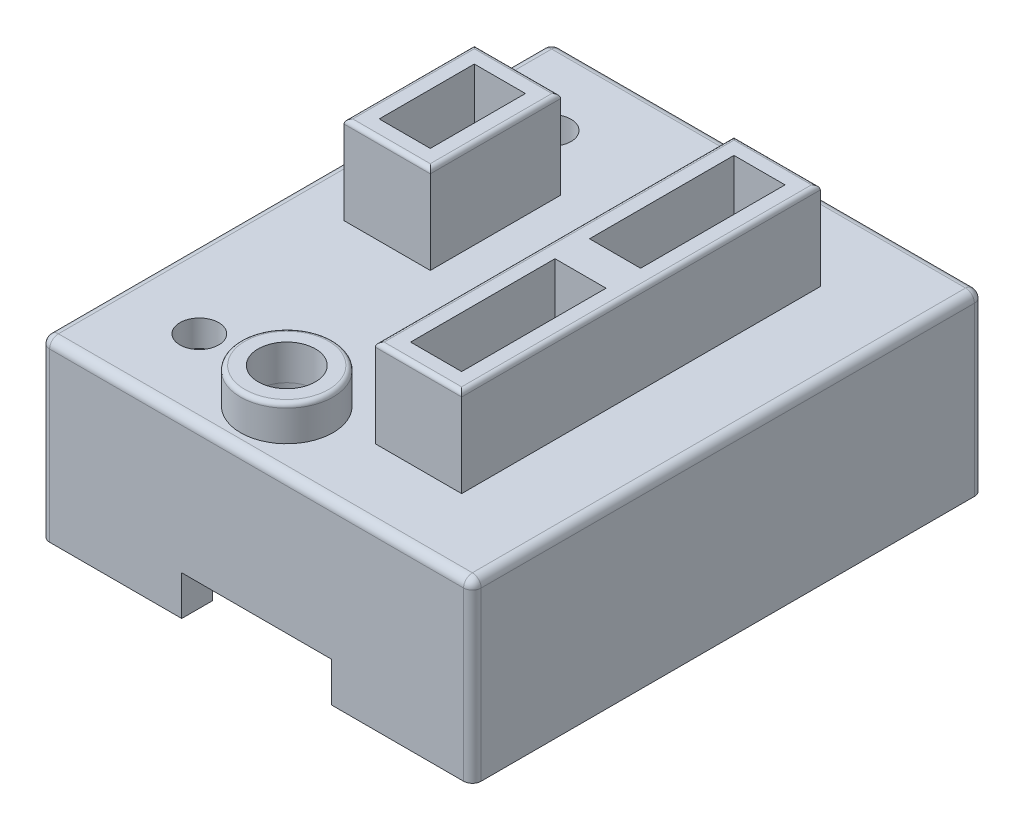
SolidWorks part; units mm, degrees
ref_plane "Front Plane" through (0, 0, 0) normal (0, 0, 1) x (1, 0, 0)
ref_plane "Top Plane" through (0, 0, 0) normal (0, 1, 0) x (1, 0, 0)
ref_plane "Right Plane" through (0, 0, 0) normal (1, 0, 0) x (0, 0, -1)
sketch "Sketch1" plane through (0, 0, 0) normal (0, 1, 0) x (1, 0, 0)
  line L0 (-15.2941, 0) -> (15.2941, 0) construction
  line L1 (-10.25, -12.5) -> (10.25, -12.5) construction
  line L2 (-10.25, -12.5) -> (-10.25, 12.5) construction
  line L3 (-10.25, 12.5) -> (10.25, 12.5) construction
  line L4 (10.25, -12.5) -> (10.25, 12.5) construction
  line L5 (-10.25, -12.5) -> (10.25, 12.5) construction
  line L6 (-10.25, 12.5) -> (10.25, -12.5) construction
  line L7 (0, 17.7941) -> (0, -15.2451) construction
  line L9 (3.6542, 0.7468) -> (6.5542, 0.7468) construction
  line L10 (3.6542, 0.7468) -> (3.6542, 8.9468) construction
  line L11 (3.6542, 8.9468) -> (6.5542, 8.9468) construction
  line L12 (6.5542, 0.7468) -> (6.5542, 8.9468) construction
  line L13 (3.6542, 0.7468) -> (6.5542, 8.9468) construction
  line L14 (3.6542, 8.9468) -> (6.5542, 0.7468) construction
  line L15 (3.6542, -9.4132) -> (6.5542, -9.4132) construction
  line L16 (3.6542, -9.4132) -> (3.6542, -1.2132) construction
  line L17 (3.6542, -1.2132) -> (6.5542, -1.2132) construction
  line L18 (6.5542, -9.4132) -> (6.5542, -1.2132) construction
  line L19 (3.6542, -9.4132) -> (6.5542, -1.2132) construction
  line L20 (3.6542, -1.2132) -> (6.5542, -9.4132) construction
  line L21 (-8.2076, 0.6688) -> (-5.3076, 0.6688) construction
  line L22 (-8.2076, 0.6688) -> (-8.2076, 6.0688) construction
  line L23 (-8.2076, 6.0688) -> (-5.3076, 6.0688) construction
  line L24 (-5.3076, 0.6688) -> (-5.3076, 6.0688) construction
  line L25 (-8.2076, 0.6688) -> (-5.3076, 6.0688) construction
  line L26 (-8.2076, 6.0688) -> (-5.3076, 0.6688) construction
  circle A0 centre (-7.75, 10) radius 1.1 construction
  circle A1 centre (-7.75, -10) radius 1.1 construction
  point P0 (0, 0)
  point P14 (5.1042, 4.8468)
  point P19 (5.1042, -5.3132)
  point P25 (-6.7576, 3.3688)
  point P32 (-1.7156, -11.0712)
  dimension "D5" = 2.2
  dimension "D1" = 25
  dimension "D2" = 20.5
  dimension "D3" = 2.5
  dimension "D4" = 2.5
  dimension "D6" = 8.2
  dimension "D7" = 2.9
  dimension "D8" = 7.6532
  dimension "D9" = 15.3542
  dimension "D10" = 17.8132
  dimension "D11" = 5.4
  dimension "D12" = 3.4924
  dimension "D13" = 9.1312
  dimension "D14" = 8.5344
  dimension "D15" = 23.5712
sketch "Sketch2" plane through (0, 0, 0) normal (0, 1, 0) x (1, 0, 0)
  line L0 (-12.25, 14.5) -> (12.25, 14.5)
  line L5 (-10.25, -12.5) -> (10.25, 12.5) construction
  line L6 (-10.25, 12.5) -> (10.25, -12.5) construction
  line L7 (12.25, -14.5) -> (12.25, 14.5)
  line L8 (-12.25, -14.5) -> (12.25, -14.5)
  line L9 (-12.25, -14.5) -> (-12.25, 14.5)
  point P0 (0, 0)
extrude "Boss-Extrude1" add sketch "Sketch2" against normal blind 10
sketch "Sketch3" plane through (0, -10, 0) normal (0, -1, 0) x (1, 0, 0)
  line L0 (-10.5, 12.75) -> (10.5, 12.75)
  line L5 (-10.25, -12.5) -> (10.25, 12.5) construction
  line L6 (-10.25, 12.5) -> (10.25, -12.5) construction
  line L7 (10.5, -12.75) -> (10.5, 12.75)
  line L8 (-10.5, -12.75) -> (10.5, -12.75)
  line L9 (-10.5, -12.75) -> (-10.5, 12.75)
  point P0 (0, 0)
extrude "Cut-Extrude1" cut sketch "Sketch3" against normal blind 8.5
sketch "Sketch4" plane through (0, 0, 0) normal (0, 1, 0) x (1, 0, 0)
  line L1 (-8.2076, 0.6688) -> (-5.3076, 0.6688)
  line L2 (-8.2076, 0.6688) -> (-8.2076, 6.0688)
  line L3 (-8.2076, 6.0688) -> (-5.3076, 6.0688)
  line L4 (-5.3076, 0.6688) -> (-5.3076, 6.0688)
  line L5 (-8.2076, 0.6688) -> (-5.3076, 6.0688) construction
  line L6 (-8.2076, 6.0688) -> (-5.3076, 0.6688) construction
  line L7 (3.6542, 0.7468) -> (6.5542, 0.7468)
  line L8 (3.6542, 0.7468) -> (3.6542, 8.9468)
  line L9 (3.6542, 8.9468) -> (6.5542, 8.9468)
  line L10 (6.5542, 0.7468) -> (6.5542, 8.9468)
  line L11 (3.6542, 0.7468) -> (6.5542, 8.9468) construction
  line L12 (3.6542, 8.9468) -> (6.5542, 0.7468) construction
  line L13 (3.6542, -9.4132) -> (6.5542, -9.4132)
  line L14 (3.6542, -9.4132) -> (3.6542, -1.2132)
  line L15 (3.6542, -1.2132) -> (6.5542, -1.2132)
  line L16 (6.5542, -9.4132) -> (6.5542, -1.2132)
  line L17 (3.6542, -9.4132) -> (6.5542, -1.2132) construction
  line L18 (3.6542, -1.2132) -> (6.5542, -9.4132) construction
  circle A0 centre (-7.75, -10) radius 1.1
  circle A1 centre (-7.75, 10) radius 1.1
  circle A2 centre (-1.7156, -11.0712) radius 1.625
  point P0 (-6.7576, 3.3688)
  point P7 (5.1042, 4.8468)
  point P14 (5.1042, -5.3132)
  dimension "D1" = 3.25
extrude "Cut-Extrude2" cut sketch "Sketch4" against normal through all
sketch "Sketch5" plane through (0, 0, 14.5) normal (0, 0, 1) x (1, 0, 0)
  line L0 (0, 6.5603) -> (0, -16.4986) construction
  line L1 (-12.25, -10) -> (12.25, -10) construction
  line L2 (4.25, -7.75) -> (-4.25, -7.75)
  line L3 (4.25, -7.75) -> (4.25, -10)
  line L4 (4.25, -10) -> (-4.25, -10)
  line L5 (-4.25, -7.75) -> (-4.25, -10)
  line L6 (4.25, -7.75) -> (-4.25, -10) construction
  line L7 (4.25, -10) -> (-4.25, -7.75) construction
  point P3 (0, -8.875)
  dimension "D1" = 2.25
  dimension "D2" = 8.5
extrude "Cut-Extrude3" cut sketch "Sketch5" against normal through all
fillet "Fillet1" radius 0.5 8 edges at (-12.25, -5, -14.5) (0, 0, 14.5) (-12.25, -5, 14.5) (-12.25, 0, 0) (0, 0, -14.5) (12.25, 0, 0) (12.25, -5, -14.5) (12.25, -5, 14.5)
sketch "Sketch6" plane through (0, -1.5, 0) normal (0, -1, 0) x (1, 0, 0)
  line L0 (-10.5, 12.75) -> (-10.5, -12.75) construction
  line L1 (-10.5, -2) -> (-9, -2)
  line L2 (-10.5, -2) -> (-10.5, -4)
  line L3 (-10.5, -4) -> (-9, -4)
  line L4 (-9, -2) -> (-9, -4)
  line L5 (-15.2941, 0) -> (15.2941, 0) construction
  line L6 (10.5, -12.75) -> (10.5, 12.75) construction
  line L7 (10.5, 7.5) -> (9, 7.5)
  line L8 (10.5, 7.5) -> (10.5, 5.5)
  line L9 (10.5, 5.5) -> (9, 5.5)
  line L10 (9, 7.5) -> (9, 5.5)
  line L12 (10.5, -4.5) -> (9, -4.5)
  line L13 (10.5, -4.5) -> (10.5, -6.5)
  line L14 (10.5, -6.5) -> (9, -6.5)
  line L15 (9, -4.5) -> (9, -6.5)
  dimension "D1" = 2
  dimension "D2" = 1.5
  dimension "D3" = 2
  dimension "D4" = 5.5
  dimension "D5" = 4.5
extrude "Boss-Extrude2" add sketch "Sketch6" along normal blind 2.7
fillet "Fillet2" radius 0.5 21 edges at (-9.75, -1.5, -2) (9.75, -1.5, -6.5) (9.75, -1.5, 5.5) (-9, -1.5, -3) (9, -1.5, -5.5) (9, -1.5, 6.5) (-9.75, -1.5, -4) (-10.5, -2.85, -4) (-9, -2.85, -4) (-9, -2.85, -2) (-10.5, -2.85, -2) (9.75, -1.5, -4.5) (10.5, -2.85, -4.5) (9, -2.85, -4.5) (9, -2.85, -6.5) (10.5, -2.85, -6.5) (9.75, -1.5, 7.5) (10.5, -2.85, 7.5) (9, -2.85, 7.5) (9, -2.85, 5.5) (10.5, -2.85, 5.5)
sketch "Sketch7" plane through (0, 0, 0) normal (0, 1, 0) x (1, 0, 0)
  line L0 (-9.2076, -0.3312) -> (-9.2076, 7.0688)
  line L1 (-8.2076, 0.6688) -> (-5.3076, 0.6688)
  line L2 (-8.2076, 0.6688) -> (-8.2076, 6.0688)
  line L3 (-8.2076, 6.0688) -> (-5.3076, 6.0688)
  line L4 (-5.3076, 0.6688) -> (-5.3076, 6.0688)
  line L5 (-9.2076, 7.0688) -> (-4.3076, 7.0688)
  line L6 (-4.3076, -0.3312) -> (-4.3076, 7.0688)
  line L7 (-9.2076, -0.3312) -> (-4.3076, -0.3312)
  line L8 (2.6542, 9.9468) -> (7.5542, 9.9468)
  line L9 (3.6542, -9.4132) -> (6.5542, -9.4132)
  line L10 (3.6542, -9.4132) -> (3.6542, -1.2132)
  line L11 (3.6542, 8.9468) -> (6.5542, 8.9468)
  line L12 (6.5542, -9.4132) -> (6.5542, -1.2132)
  line L13 (7.5542, -10.4132) -> (7.5542, 9.9468)
  line L14 (2.6542, -10.4132) -> (7.5542, -10.4132)
  line L15 (2.6542, -10.4132) -> (2.6542, 9.9468)
  line L16 (3.6542, 0.7468) -> (3.6542, 8.9468)
  line L17 (3.6542, -1.2132) -> (6.5542, -1.2132)
  line L19 (3.6542, 0.7468) -> (6.5542, 0.7468)
  line L21 (6.5542, 0.7468) -> (6.5542, 8.9468)
  line L22 (3.6542, -9.4132) -> (3.6542, 8.9468) construction
  line L24 (6.5542, -9.4132) -> (6.5542, 8.9468) construction
  dimension "D1" = 1
  dimension "D2" = 1
extrude "Boss-Extrude3" add sketch "Sketch7" along normal blind 5
sketch "Sketch8" plane through (0, 0, 0) normal (0, 1, 0) x (1, 0, 0)
  circle A0 centre (-1.7156, -11.0712) radius 1.625
  circle A1 centre (-1.7156, -11.0712) radius 2.625
  dimension "D1" = 1
extrude "Boss-Extrude4" add sketch "Sketch8" along normal blind 2 separate body
fillet "Fillet3" radius 0.25 8 edges at (-6.7576, 5, 0.3312) (-4.3076, 5, -3.3688) (-9.2076, 5, -3.3688) (-6.7576, 5, -7.0688) (5.1042, 5, -9.9468) (7.5542, 5, 0.2332) (5.1042, 5, 10.4132) (2.6542, 5, 0.2332)
fillet "Fillet4" radius 0.25 1 edges at (-1.7156, 2, 13.6962)
